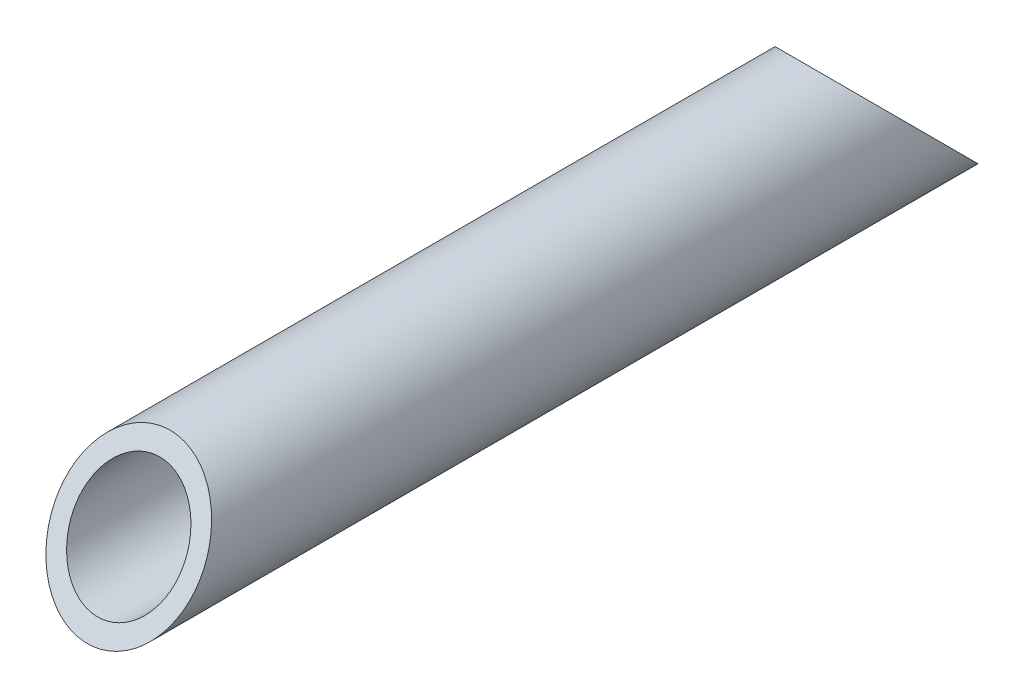
SolidWorks part; units mm, degrees
ref_plane "Front Plane" through (0, 0, 0) normal (0, 0, 1) x (1, 0, 0)
ref_plane "Top Plane" through (0, 0, 0) normal (0, 1, 0) x (1, 0, 0)
ref_plane "Right Plane" through (0, 0, 0) normal (1, 0, 0) x (0, 0, -1)
sketch "Sketch1" plane through (0, 0, 0) normal (0, 0, 1) x (1, 0, 0)
  circle A0 centre (0, 0) radius 6.35
  circle A1 centre (0, 0) radius 4.7625
  dimension "D1" = 12.7
  dimension "D2" = 9.525
extrude "Boss-Extrude1" add sketch "Sketch1" along normal blind 76.2
sketch "Sketch2" plane through (0, 0, 0) normal (1, 0, 0) x (0, 0, -1)
  line L0 (-76.2, -6.35) -> (-68.8677, 6.35)
  line L1 (0, 6.35) -> (-76.2, 6.35) construction
  line L2 (-68.8677, 6.35) -> (-76.2, 6.35)
  line L3 (-76.2, 6.35) -> (-76.2, -6.35)
  dimension "D1" = 60
extrude "Cut-Extrude1" cut sketch "Sketch2" against normal mid plane 76.2
sketch "Sketch3" plane through (0, 0, 0) normal (1, 0, 0) x (0, 0, -1)
  line L0 (-12.7, 6.35) -> (0, -6.35)
  line L1 (0, 6.35) -> (-68.8677, 6.35) construction
  line L2 (0, -6.35) -> (0, 6.35)
  line L3 (0, 6.35) -> (-12.7, 6.35)
  dimension "D1" = 45
extrude "Cut-Extrude3" cut sketch "Sketch3" against normal mid plane 76.2
ref_plane "Plane1" through (0, 6.35, 0) normal (0, 1, 0) x (1, 0, 0)
